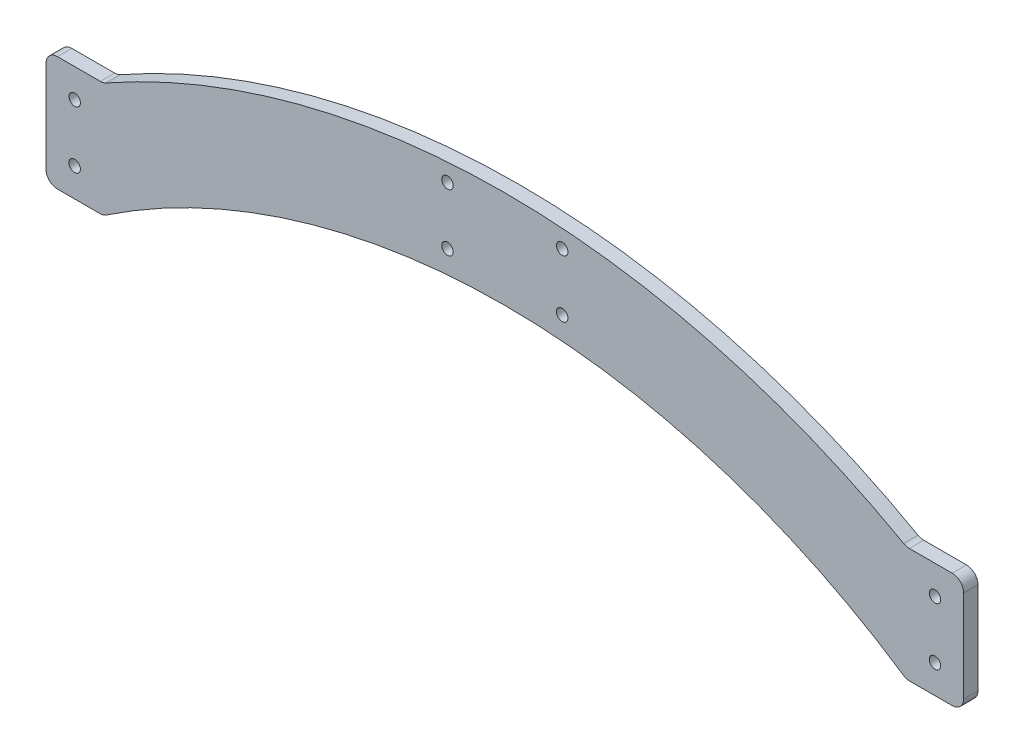
SolidWorks part; units mm, degrees
ref_plane "Plan de face" through (0, 0, 0) normal (0, 0, 1) x (1, 0, 0)
ref_plane "Plan de dessus" through (0, 0, 0) normal (0, 1, 0) x (1, 0, 0)
ref_plane "Plan de droite" through (0, 0, 0) normal (1, 0, 0) x (0, 0, -1)
sketch "Esquisse1" plane through (0, 0, 0) normal (0, 0, 1) x (1, 0, 0)
  line L0 (-140, 0) -> (140, 0) construction
  line L2 (160, 0) -> (160, 40)
  line L3 (0, 62.4131) -> (0, -5.9928) construction
  line L4 (177.3754, 20) -> (-176.3402, 20) construction
  line L5 (-160, 0) -> (-160, 40)
  line L9 (-140, 40) -> (140, 40) construction
  line L10 (20, 70) -> (20, 50) construction
  line L11 (20, 70) -> (-20, 70) construction
  line L12 (20, 60) -> (-20, 60) construction
  line L13 (-140, 40) -> (-160, 40)
  line L14 (-140, 0) -> (-160, 0)
  line L15 (140, 40) -> (160, 40)
  line L16 (140, 0) -> (160, 0)
  arc A1 (140, 40) -> (-140, 40) centre (0, -207.1232) ccw
  arc A2 (140, 0) -> (-140, 0) centre (0, -207.1232) ccw
  circle A5 centre (20, 70) radius 2
  circle A6 centre (20, 50) radius 2
  circle A8 centre (-20, 50) radius 2
  circle A9 centre (-20, 70) radius 2
  circle A10 centre (150, 30) radius 2
  circle A11 centre (150, 10) radius 2
  circle A12 centre (-150, 10) radius 2
  circle A13 centre (-150, 30) radius 2
  point P0 (-135, 0)
  point P8 (0, 40)
  point P15 (132.0149, 0)
  point P17 (135, 0)
  point P23 (0, 0)
  point P25 (160, 20)
  point P26 (0, 0)
  point P41 (-160, 20)
  point P42 (135, 40)
  point P43 (-135, 40)
  point P45 (140, 38.4941)
  dimension "D5" = 250
  dimension "D9" = 4
  dimension "D1" = 300
  dimension "D2" = 20
  dimension "D3" = 20
  dimension "D4" = 5
  dimension "D6" = 40
  dimension "D7" = 20
  dimension "D8" = 40
  dimension "D10" = 10
  dimension "D11" = 10
extrude "Boss.-Extru.1" add sketch "Esquisse1" along normal blind 5
fillet "Congé1" radius 4 8 edges at (-160, 40, 2.5) (-160, 0, 2.5) (160, 0, 2.5) (160, 40, 2.5) (-140, 40, 2.5) (-140, 0, 2.5) (140, 40, 2.5) (140, 0, 2.5)
